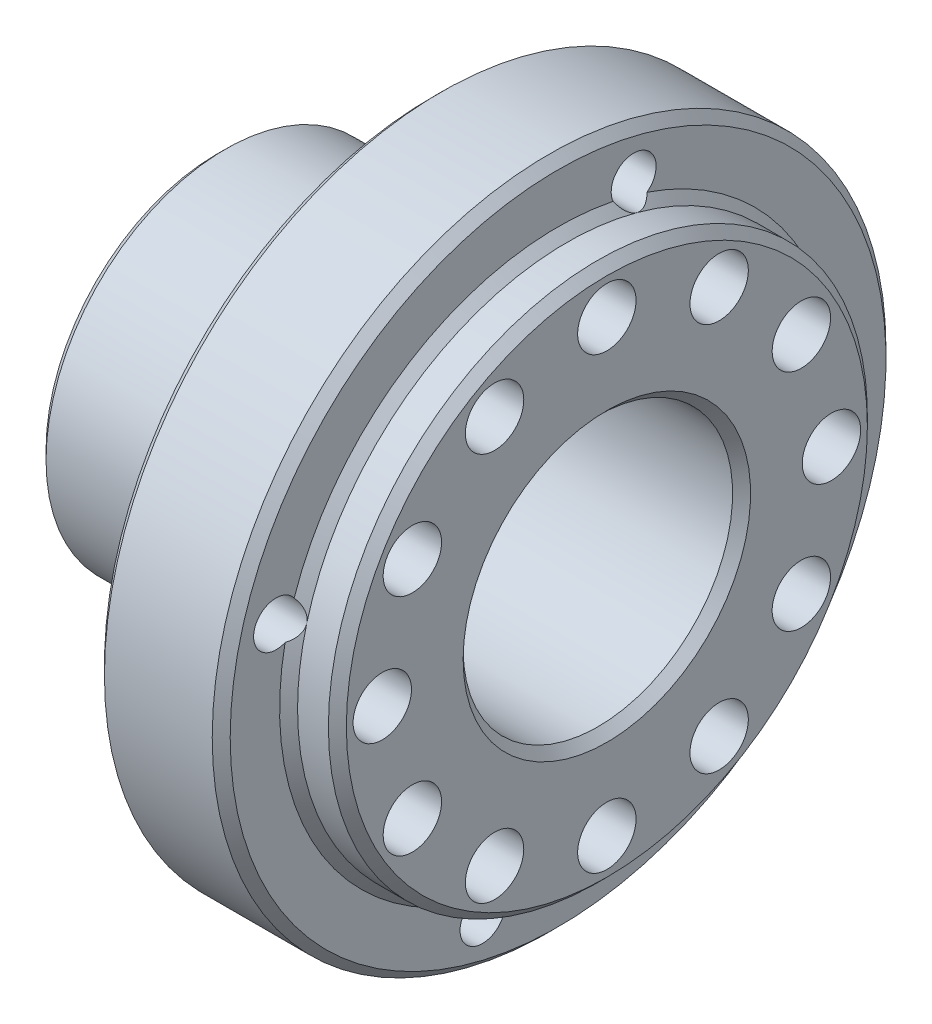
SolidWorks part; units mm, degrees
material "2014 Alloy"
ref_plane "Front Plane" through (0, 0, 0) normal (0, 0, 1) x (1, 0, 0)
ref_plane "Top Plane" through (0, 0, 0) normal (0, 1, 0) x (1, 0, 0)
ref_plane "Right Plane" through (0, 0, 0) normal (1, 0, 0) x (0, 0, -1)
sketch "Sketch1" plane through (0, 0, 0) normal (0, 1, 0) x (1, 0, 0)
  line L0 (0, 20) -> (24, 20)
  line L1 (24, 20) -> (24, 30)
  line L2 (24, 30) -> (43.43, 30)
  line L3 (43.43, 30) -> (43.43, 15)
  line L5 (0, 15) -> (0, 20)
  line L6 (0, 0) -> (28.2243, 0) construction
  line L7 (0, 15) -> (43.43, 15)
  dimension "D1" = 40
  dimension "D3" = 24
  dimension "D4" = 60
  dimension "D5" = 43.43
  dimension "D6" = 30
revolve "Revolve1" add sketch "Sketch1" angle 360 about L6
sketch "Sketch2" plane through (43.43, 0, 0) normal (1, 0, 0) x (0, 0, -1)
  circle A0 centre (0, 25) radius 3.25
  circle A1 centre (25, 0) radius 3.25
  circle A2 centre (-25, 0) radius 3.25
  circle A3 centre (0, -25) radius 3.25
  circle A4 centre (0, 0) radius 25 construction
  dimension "D1" = 6.5
  dimension "D2" = 50
extrude "Cut-Extrude1" cut sketch "Sketch2" against normal through all
sketch "Sketch4" plane through (24, 0, 0) normal (-1, 0, 0) x (0, 0, 1)
  circle A0 centre (0, 0) radius 37.5
  circle A1 centre (0, 0) radius 30 construction
  circle A2 centre (0, 0) radius 30
  dimension "D1" = 75
extrude "Boss-Extrude1" add sketch "Sketch4" against normal blind 14
chamfer "Chamfer1" distance 1 angle 45 8 edges at (38, 0, 30) (38, 0, 37.5) (24, 0, 37.5) (0, 0, 15) (43.43, 0, 15) (43.43, 0, 30) (24, 0, 20) (0, 0, 20)
pattern_circular "CirPattern1" count 3 every 30 about axis through (0, 0, 0) along (1, 0, 0) of "Cut-Extrude1"
hole_wizard "M6 Tapped Hole1" positions "Sketch8" profile "Sketch7" tap size "M6" standard "ISO" end condition through all
sketch "Sketch8" plane through (24, 0, 0) normal (-1, 0, 0) x (0, 0, 1)
  line L0 (-31.3926, -8.4116) -> (-8.4116, 31.3926)
  line L1 (-31.3926, -8.4116) -> (8.4116, -31.3926)
  line L2 (-8.4116, 31.3926) -> (31.3926, 8.4116)
  line L3 (8.4116, -31.3926) -> (31.3926, 8.4116)
  line L4 (-8.4116, 31.3926) -> (8.4116, -31.3926) construction
  line L5 (0, 0) -> (7.1475, 0) construction
  line L7 (-12.5, 21.6506) -> (-8.4116, 31.3926) construction
  line L8 (-8.4116, 31.3926) -> (0, 25) construction
  circle A0 centre (0, 25) radius 3.25 construction
  circle A1 centre (-12.5, 21.6506) radius 3.25 construction
  point P0 (-8.4116, 31.3926)
  point P2 (31.3926, 8.4116)
  point P4 (8.4116, -31.3926)
  point P6 (-31.3926, -8.4116)
  dimension "D1" = 65
sketch "Sketch7" plane through (24, 31.3926, -8.4116) normal (0, 1, 0) x (0, 0, 1)
  line L0 (0, 0) -> (0, 19.43)
  line L1 (0, 19.43) -> (2.5, 19.43)
  line L2 (2.5, 19.43) -> (2.5, 0)
  line L5 (2.5, 0) -> (0, 0)
  line L11 (0, -6.35) -> (0, 107.95) construction
  dimension "Thread Major Dia." = 5
  dimension "Thru Tap Drill Depth" = 19.43
